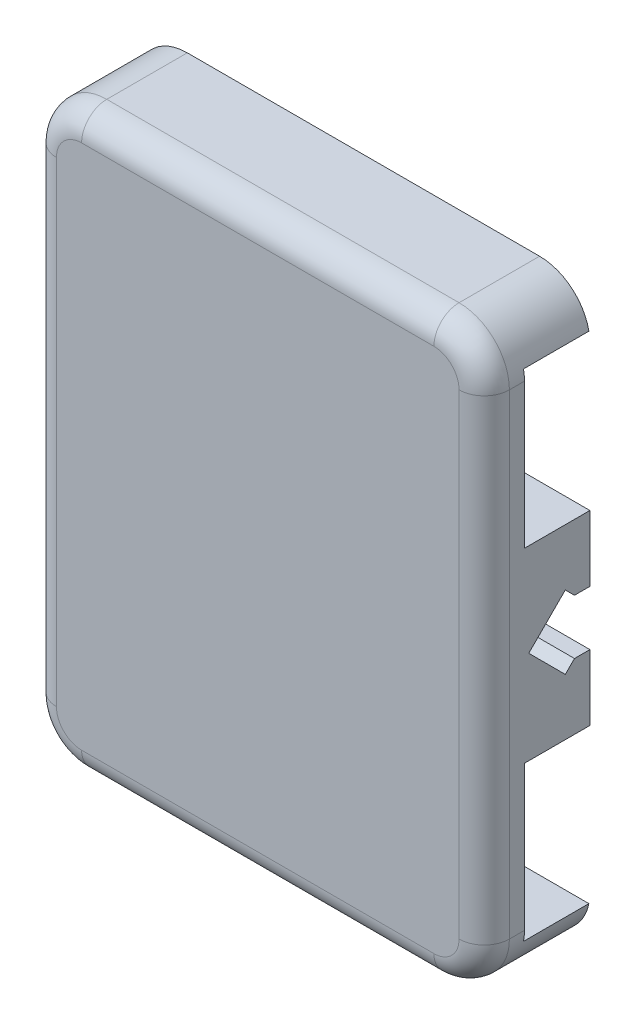
SolidWorks part; units mm, degrees
ref_plane "Front Plane" through (0, 0, 0) normal (0, 0, 1) x (1, 0, 0)
ref_plane "Top Plane" through (0, 0, 0) normal (0, 1, 0) x (1, 0, 0)
ref_plane "Right Plane" through (0, 0, 0) normal (1, 0, 0) x (0, 0, -1)
sketch "Sketch1" plane through (0, 0, 0) normal (0, 0, 1) x (1, 0, 0)
  line L0 (-8.5573, -7.5564) -> (9.4427, -7.5564) construction
  line L1 (-8.5573, 2.2936) -> (9.4427, 2.2936)
  line L2 (-8.5573, 2.2936) -> (-8.5573, -17.4064)
  line L3 (-8.5573, -17.4064) -> (9.4427, -17.4064)
  line L4 (9.4427, 2.2936) -> (9.4427, -17.4064)
  line L5 (-5.2573, -11.2564) -> (-8.5573, -11.2564)
  line L6 (-5.2573, -11.2564) -> (-5.2573, -3.8564)
  line L7 (-8.5573, -11.2564) -> (-8.5573, -3.8564)
  line L8 (-5.2573, -3.8564) -> (-8.5573, -3.8564)
  line L9 (-5.2573, -11.2564) -> (-8.5573, -3.8564) construction
  line L10 (-8.5573, -11.2564) -> (-5.2573, -3.8564) construction
  line L11 (0.4427, 3.8936) -> (0.4427, -17.4064) construction
  line L12 (6.1427, -3.8564) -> (9.4427, -3.8564)
  line L13 (6.1427, -3.8564) -> (6.1427, -11.2564)
  line L14 (6.1427, -11.2564) -> (9.4427, -11.2564)
  line L15 (9.4427, -3.8564) -> (9.4427, -11.2564)
  line L16 (-8.5573, 2.2936) -> (9.4427, 2.2936)
  line L17 (-8.5573, 2.2936) -> (-8.5573, 3.8936)
  line L18 (-8.5573, 3.8936) -> (9.4427, 3.8936)
  line L19 (9.4427, 2.2936) -> (9.4427, 3.8936)
  line L20 (-8.5573, -17.4064) -> (9.4427, -17.4064)
  line L21 (-8.5573, -17.4064) -> (-8.5573, -19.0064)
  line L22 (-8.5573, -19.0064) -> (9.4427, -19.0064)
  line L23 (9.4427, -17.4064) -> (9.4427, -19.0064)
  line L24 (-1.2073, -11.2564) -> (2.0927, -11.2564)
  line L25 (-1.2073, -11.2564) -> (-1.2073, -3.8564)
  line L26 (2.0927, -11.2564) -> (2.0927, -3.8564)
  line L27 (-1.2073, -3.8564) -> (2.0927, -3.8564)
  line L28 (-1.2073, -11.2564) -> (2.0927, -3.8564) construction
  line L29 (2.0927, -11.2564) -> (-1.2073, -3.8564) construction
  point P7 (-6.9073, -7.5564)
  point P22 (0.4427, -7.5564)
  dimension "D1" = 18
  dimension "D2" = 19.7
  dimension "D4" = 7.4
  dimension "D6" = 3.3
  dimension "D7" = 1.6
  dimension "D8" = 1.6
extrude "Boss-Extrude1" add sketch "Sketch1" along normal blind 2.6 contours L6 L8 L2 L5 | L27 L25 L24 L26 | L13 L14 L4 L12 | L1 L19 L18 L17 | L23 L3 L21 L22
sketch "Sketch3" plane through (0, 0, 2.6) normal (0, 0, 1) x (1, 0, 0)
  line L1 (-8.5573, 3.8936) -> (9.4427, 3.8936)
  line L2 (-8.5573, 3.8936) -> (-8.5573, -19.0064)
  line L3 (-8.5573, -19.0064) -> (9.4427, -19.0064)
  line L4 (9.4427, 3.8936) -> (9.4427, -19.0064)
extrude "Boss-Extrude2" add sketch "Sketch3" along normal blind 1.6
sketch "Sketch4" plane through (-8.5573, 0, 0) normal (-1, 0, 0) x (0, 0, 1)
  line L0 (0, -7.5564) -> (4.2, -7.5564) construction
  line L1 (0, -3.8564) -> (0, -11.2564) construction
  line L2 (4.2, 3.8936) -> (4.2, -19.0064) construction
  line L3 (-0.4745, -7.5564) -> (0.9779, -6.104)
  line L4 (-0.4745, -7.5564) -> (0.9779, -9.0088)
  line L5 (0.9779, -6.104) -> (2.4303, -7.5564)
  line L6 (0.9779, -9.0088) -> (2.4303, -7.5564)
  line L7 (-0.4745, -7.5564) -> (2.4303, -7.5564) construction
  line L8 (0.9779, -6.104) -> (0.9779, -9.0088) construction
  line L10 (-0.631, -6.4685) -> (1.3424, -6.4685)
  line L11 (-0.631, -6.4685) -> (-0.631, -8.6443)
  line L12 (-0.631, -8.6443) -> (1.3424, -8.6443)
  line L13 (1.3424, -6.4685) -> (1.3424, -8.6443)
  line L14 (-0.631, -6.4685) -> (1.3424, -8.6443) construction
  line L15 (-0.631, -8.6443) -> (1.3424, -6.4685) construction
  point P7 (0.9779, -7.5564)
  point P9 (0.3557, -7.5564)
  line M7 (0, -3.8564) -> (0, -11.2564)
extrude "Cut-Extrude1" cut sketch "Sketch4" against normal through all both and the other way through all contours L12 L4 L6 | L5 L13 L6 | L3 L10 L5 | L13 L10 L3 L4 L12 M7 | L10 L3 M7 | L12 L4 M7
fillet "Fillet1" radius 2 4 edges at (-8.5573, 3.8936, 2.1) (9.4427, 3.8936, 2.1) (9.4427, -19.0064, 2.1) (-8.5573, -19.0064, 2.1)
fillet "Fillet2" radius 1 8 edges at (8.8569, 3.3078, 4.2) (9.4427, -7.5564, 4.2) (8.8569, -18.4206, 4.2) (0.4427, -19.0064, 4.2) (-7.9715, -18.4206, 4.2) (-8.5573, -7.5564, 4.2) (-7.9715, 3.3078, 4.2) (0.4427, 3.8936, 4.2)
